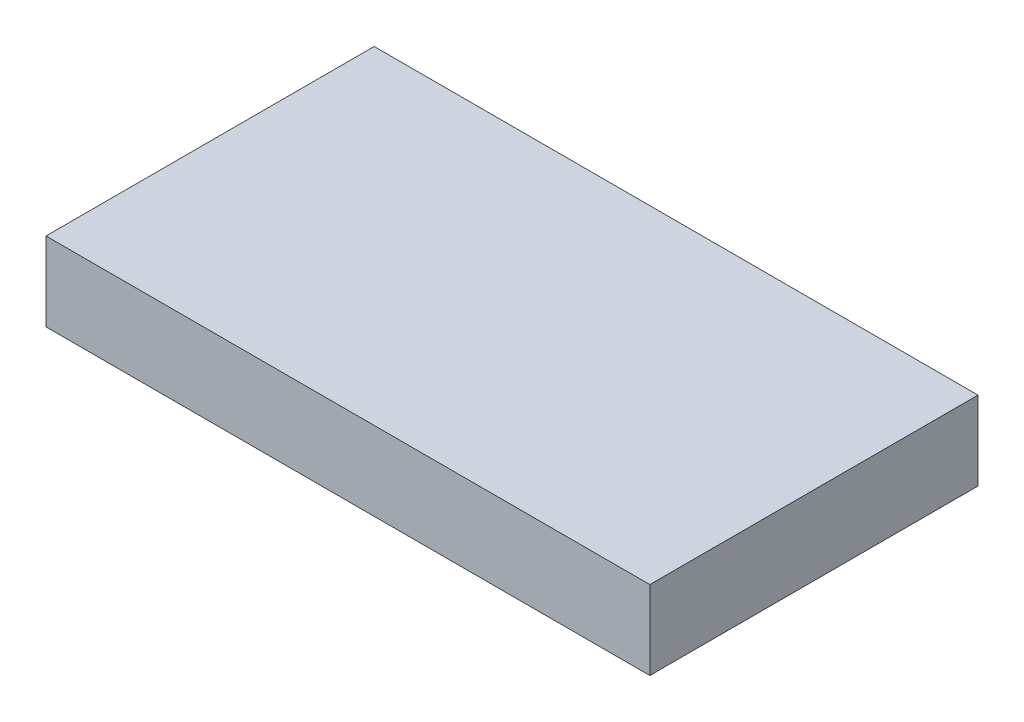
SolidWorks part; units mm, degrees
ref_plane "Front Plane" through (0, 0, 0) normal (0, 0, 1) x (1, 0, 0)
ref_plane "Top Plane" through (0, 0, 0) normal (0, 1, 0) x (1, 0, 0)
ref_plane "Right Plane" through (0, 0, 0) normal (1, 0, 0) x (0, 0, -1)
sketch "Sketch1" plane through (0, 0, 0) normal (1, 0, 0) x (0, 0, -1)
  line L1 (-6.25, 1.5) -> (6.25, 1.5)
  line L2 (-6.25, 1.5) -> (-6.25, -1.5)
  line L3 (-6.25, -1.5) -> (6.25, -1.5)
  line L4 (6.25, 1.5) -> (6.25, -1.5)
  line L5 (-6.25, 1.5) -> (6.25, -1.5) construction
  line L6 (-6.25, -1.5) -> (6.25, 1.5) construction
  point P0 (0, 0)
  dimension "D1" = 12.5
  dimension "D2" = 3
extrude "Boss-Extrude1" add sketch "Sketch1" against normal blind 23
